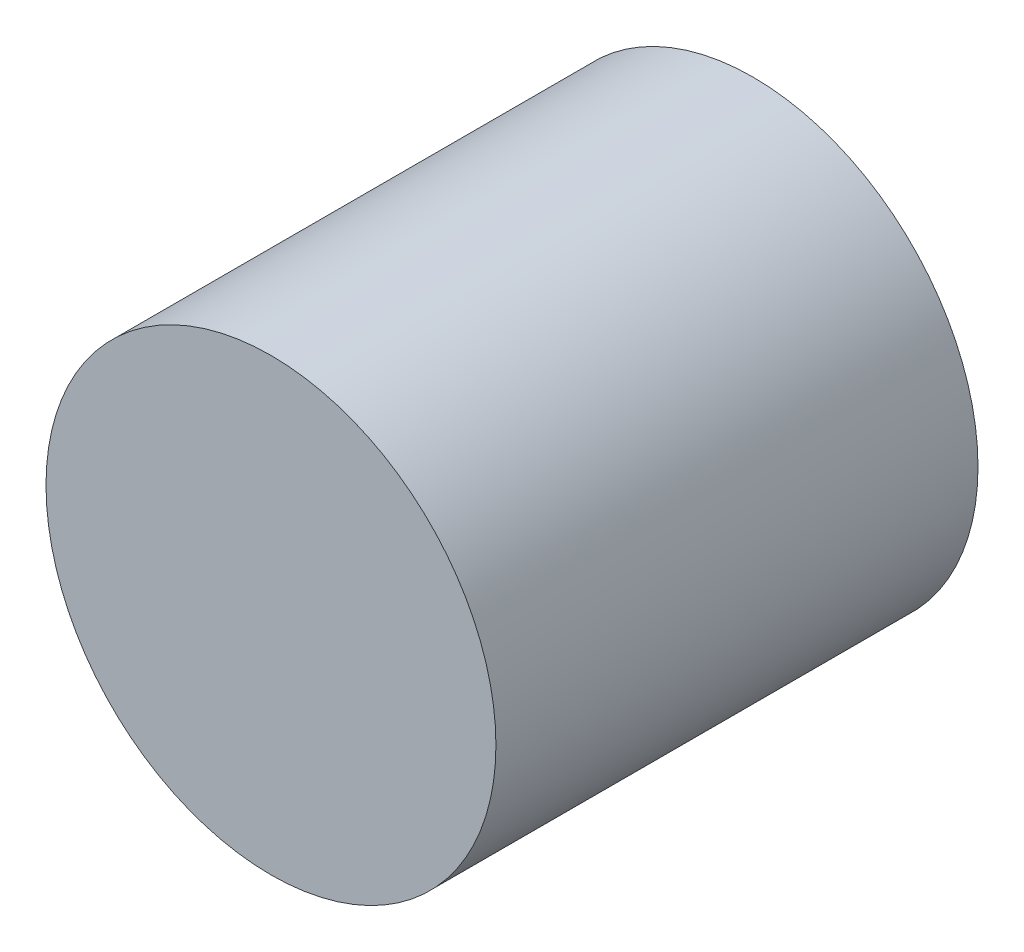
SolidWorks part; units mm, degrees
ref_plane "Front Plane" through (0, 0, 0) normal (0, 0, 1) x (1, 0, 0)
ref_plane "Top Plane" through (0, 0, 0) normal (0, 1, 0) x (1, 0, 0)
ref_plane "Right Plane" through (0, 0, 0) normal (1, 0, 0) x (0, 0, -1)
sketch "Sketch1" plane through (0, 0, 0) normal (0, 0, 1) x (1, 0, 0)
  circle A0 centre (0, 0) radius 14
  dimension "D1" = 28
extrude "Boss-Extrude1" add sketch "Sketch1" along normal blind 30
